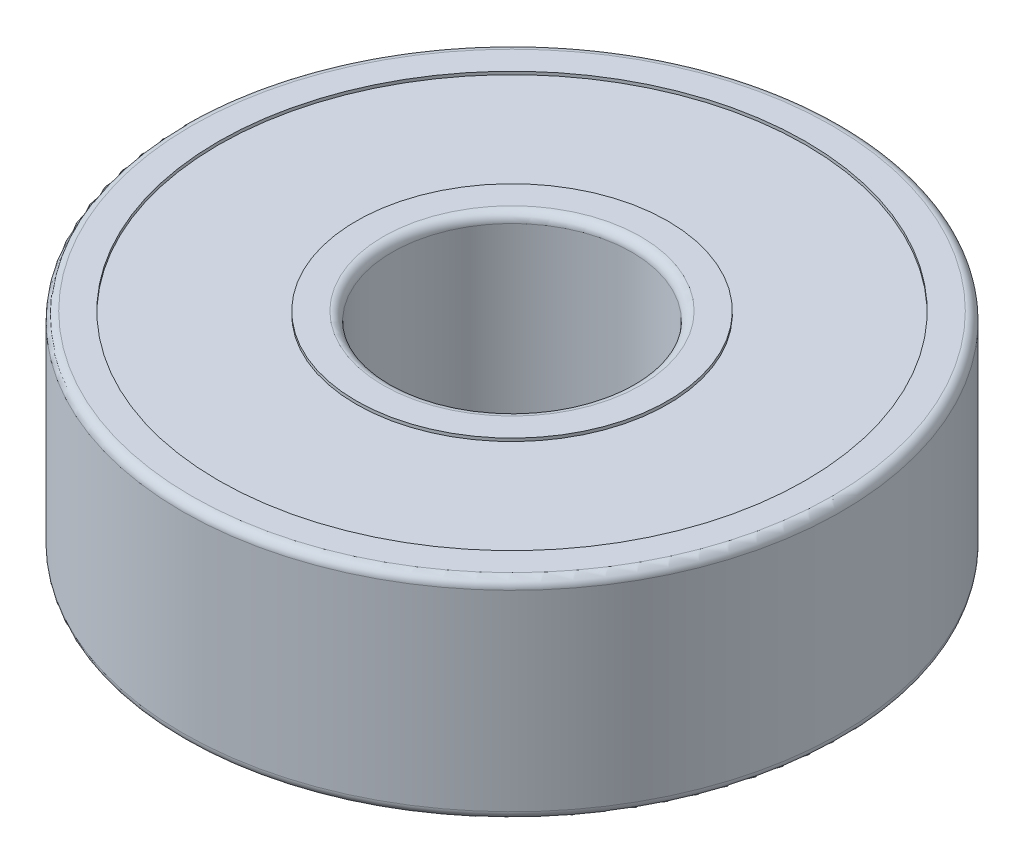
SolidWorks part; units mm, degrees
ref_plane "Alzado" through (0, 0, 0) normal (0, 0, 1) x (1, 0, 0)
ref_plane "Planta" through (0, 0, 0) normal (0, 1, 0) x (1, 0, 0)
ref_plane "Vista lateral" through (0, 0, 0) normal (1, 0, 0) x (0, 0, -1)
sketch "Croquis1" plane through (0, 0, 0) normal (0, 1, 0) x (1, 0, 0)
  circle A0 centre (0, 0) radius 4
  circle A1 centre (0, 0) radius 11
  dimension "D1" = 22
  dimension "D2" = 8
extrude "Saliente-Extruir1" add sketch "Croquis1" along normal blind 7
sketch "Croquis2" plane through (0, 7, 0) normal (0, 1, 0) x (1, 0, 0)
  circle A0 centre (0, 0) radius 9.8
  circle A1 centre (0, 0) radius 5.2
  circle A2 centre (0, 0) radius 4 construction
  circle A3 centre (0, 0) radius 11 construction
  dimension "D1" = 1.2
  dimension "D2" = 1.2
extrude "Cortar-Extruir1" cut sketch "Croquis2" against normal blind 0.1
ref_plane "Plano1" through (0, 3.5, 0) normal (0, 1, 0) x (1, 0, 0)
mirror "Simetría1" about plane through (0, 3.5, 0) normal (0, 1, 0) of "Cortar-Extruir1"
fillet "Redondeo1" radius 0.3 4 edges at (0, 0, 11) (0, 7, 11) (0, 0, 4) (0, 7, 4)
